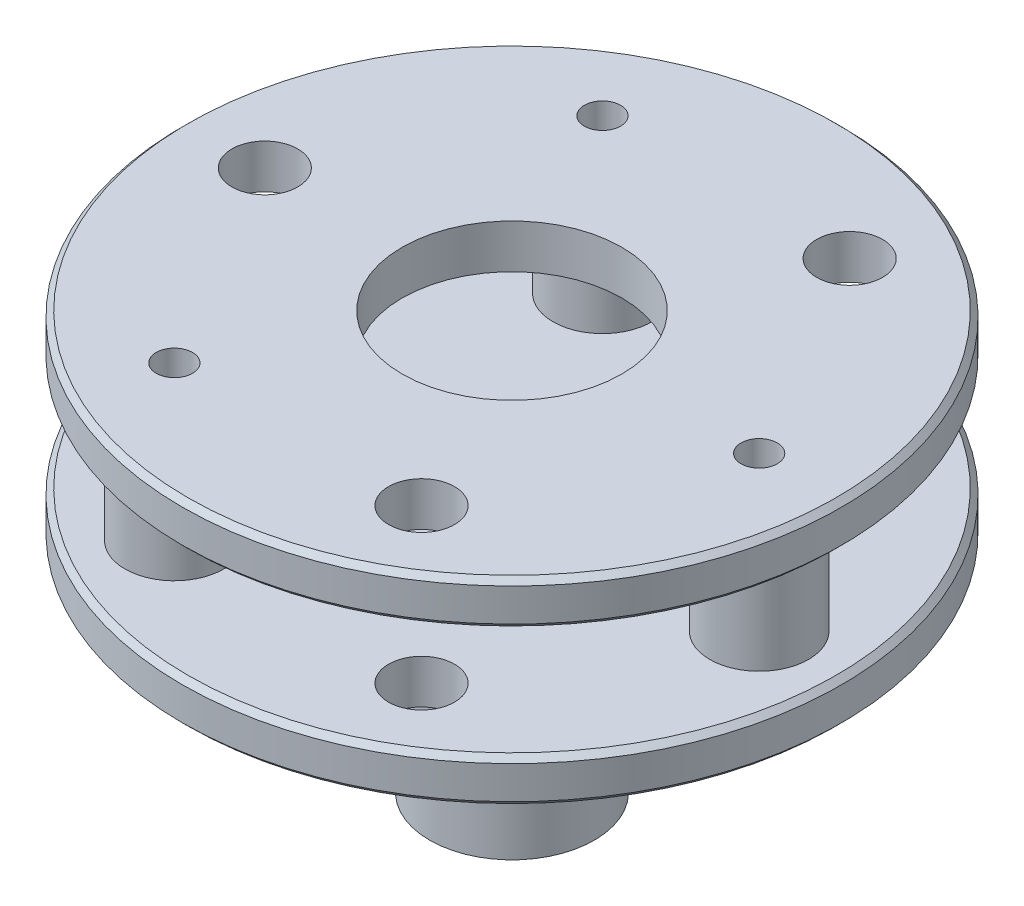
SolidWorks part; units mm, degrees
ref_plane "前视基准面" through (0, 0, 0) normal (0, 0, 1) x (1, 0, 0)
ref_plane "上视基准面" through (0, 0, 0) normal (0, 1, 0) x (1, 0, 0)
ref_plane "右视基准面" through (0, 0, 0) normal (1, 0, 0) x (0, 0, -1)
ref_plane "基准面1" through (0, 40, 0) normal (0, 1, 0) x (1, 0, 0)
sketch "草图1" plane through (0, 40, 0) normal (0, 1, 0) x (1, 0, 0)
  circle A0 centre (0, 0) radius 60
extrude "凸台-拉伸1" add sketch "草图1" along normal blind 8
ref_plane "基准面2" through (0, 68, 0) normal (0, 1, 0) x (1, 0, 0)
sketch "草图3" plane through (0, 40, 0) normal (0, 1, 0) x (1, 0, 0)
  circle A0 centre (45, 0) radius 9
  circle A1 centre (-22.5, -38.9711) radius 9
  circle A2 centre (-22.5, 38.9711) radius 9
extrude "凸台-拉伸3" add sketch "草图3" along normal blind 36
sketch "草图4" plane through (0, 68, 0) normal (0, 1, 0) x (1, 0, 0)
  circle A0 centre (0, 0) radius 60
extrude "凸台-拉伸4" add sketch "草图4" along normal blind 8
sketch "草图5" plane through (0, 0, 0) normal (0, 1, 0) x (1, 0, 0)
  circle A0 centre (0, 0) radius 15
extrude "凸台-拉伸5" add sketch "草图5" along normal blind 48
ref_plane "基准面3" through (0, 76, 0) normal (0, 1, 0) x (1, 0, 0)
sketch "草图6" plane through (0, 76, 0) normal (0, 1, 0) x (1, 0, 0)
  circle A0 centre (45, 0) radius 3.3
  circle A1 centre (-22.5, -38.9711) radius 3.3
  circle A2 centre (-22.5, 38.9711) radius 3.3
extrude "切除-拉伸1" cut sketch "草图6" against normal through all
sketch "草图7" plane through (0, 76, 0) normal (0, 1, 0) x (1, 0, 0)
  circle A0 centre (22.5, -38.9711) radius 6
  circle A1 centre (-45, 0) radius 6
  circle A2 centre (22.5, 38.9711) radius 6
extrude "切除-拉伸2" cut sketch "草图7" against normal through all
sketch "草图8" plane through (0, 76, 0) normal (0, 1, 0) x (1, 0, 0)
  circle A0 centre (0, 0) radius 20
extrude "切除-拉伸3" cut sketch "草图8" against normal blind 8
sketch "草图9" plane through (0, 0, 0) normal (0, 1, 0) x (1, 0, 0)
  circle A0 centre (0, 0) radius 4.25
extrude "切除-拉伸4" cut sketch "草图9" along normal blind 20
chamfer "倒角1" distance 1 angle 45 4 edges at (0, 76, 60) (0, 68, 60) (0, 48, 60) (0, 40, 60)
